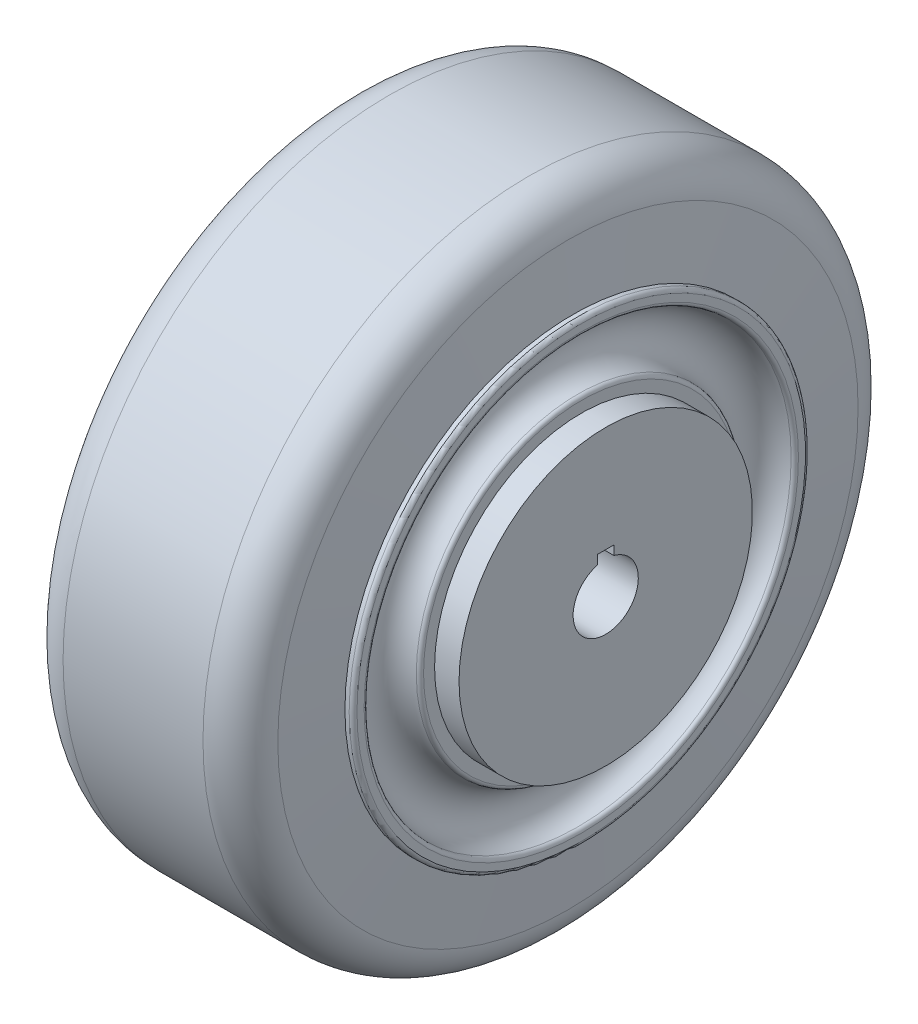
SolidWorks part; units mm, degrees
ref_plane "Front Plane" through (0, 0, 0) normal (0, 0, 1) x (1, 0, 0)
ref_plane "Top Plane" through (0, 0, 0) normal (0, 1, 0) x (1, 0, 0)
ref_plane "Right Plane" through (0, 0, 0) normal (1, 0, 0) x (0, 0, -1)
sketch "Sketch1" plane through (0, 0, 0) normal (0, 0, 1) x (1, 0, 0)
  line L0 (0, 6.35) -> (0, 28.575)
  line L1 (0, 28.575) -> (4.7625, 28.575)
  line L2 (4.7625, 28.575) -> (4.7625, 31.4325)
  line L3 (7.9375, 63.5) -> (49.2125, 63.5)
  line L4 (4.7625, 41.5925) -> (4.7625, 44.45)
  line L5 (52.3875, 28.575) -> (57.15, 28.575)
  line L6 (57.15, 28.575) -> (57.15, 6.35)
  line L7 (57.15, 6.35) -> (0, 6.35)
  line L8 (0, 0) -> (59.6601, 0) construction
  line L9 (4.7625, 44.45) -> (6.35, 44.45)
  line L10 (6.35, 44.45) -> (7.9375, 63.5)
  line L11 (52.3875, 28.575) -> (52.3875, 31.4325)
  line L12 (52.3875, 41.5925) -> (52.3875, 44.45)
  line L13 (52.3875, 44.45) -> (50.8, 44.45)
  line L14 (50.8, 44.45) -> (49.2125, 63.5)
  arc A0 (4.7625, 31.4325) -> (4.7625, 41.5925) centre (4.7625, 36.5125) ccw
  arc A1 (52.3875, 31.4325) -> (52.3875, 41.5925) centre (52.3875, 36.5125) cw
  dimension "D10" = 5.08
  dimension "D11" = 5.08
  dimension "D1" = 6.35
  dimension "D2" = 57.15
  dimension "D3" = 41.275
  dimension "D4" = 28.575
  dimension "D5" = 63.5
  dimension "D6" = 7.9375
  dimension "D7" = 4.7625
  dimension "D8" = 1.5875
  dimension "D9" = 1.5875
  dimension "D12" = 19.05
revolve "Revolve1" add sketch "Sketch1" angle 360 about L8
fillet "Fillet1" radius 7.62 2 edges at (49.2125, 0, 63.5) (7.9375, 0, 63.5)
fillet "Fillet2" radius 0.762 6 edges at (52.3875, 0, 31.4325) (52.3875, 0, 41.5925) (52.3875, 0, 44.45) (4.7625, 0, 31.4325) (4.7625, 0, 41.5925) (4.7625, 0, 44.45)
sketch "Sketch3" plane through (0, 0, 0) normal (-1, 0, 0) x (0, 0, 1)
  line L1 (1.5875, 4.7625) -> (-1.5875, 4.7625)
  line L2 (1.5875, 4.7625) -> (1.5875, 7.9375)
  line L3 (1.5875, 7.9375) -> (-1.5875, 7.9375)
  line L4 (-1.5875, 4.7625) -> (-1.5875, 7.9375)
  dimension "D1" = 3.175
  dimension "D2" = 3.175
  dimension "D3" = 1.5875
  dimension "D4" = 7.9375
extrude "Cut-Extrude1" cut sketch "Sketch3" against normal through all
